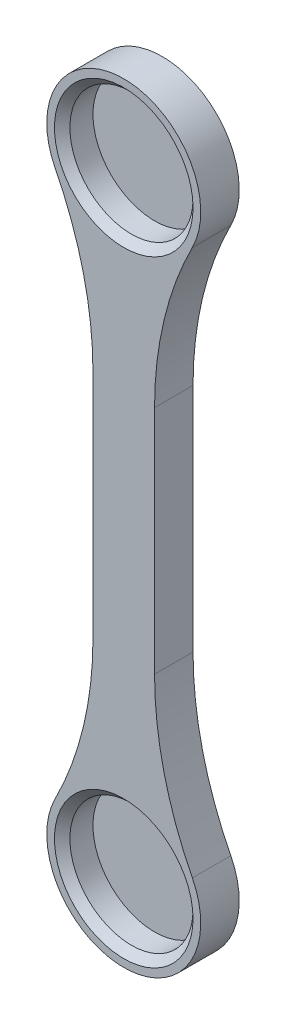
SolidWorks part; units mm, degrees
ref_plane "Plan de face" through (0, 0, 0) normal (0, 0, 1) x (1, 0, 0)
ref_plane "Plan de dessus" through (0, 0, 0) normal (0, 1, 0) x (1, 0, 0)
ref_plane "Plan de droite" through (0, 0, 0) normal (1, 0, 0) x (0, 0, -1)
sketch "Esquisse1" plane through (0, 0, 0) normal (0, 0, 1) x (1, 0, 0)
  line L0 (-10, 0) -> (-10, 80)
  line L1 (10, 0) -> (10, 80)
  arc A0 (-10, 0) -> (10, 0) centre (0, 0) ccw
  arc A1 (10, 80) -> (-10, 80) centre (0, 80) ccw
  point P9 (11.059, 55.5002)
  point P10 (0, 0)
  point P11 (0, 0)
  point P12 (-11.8706, 0)
  dimension "D1" = 80
  dimension "D2" = 10
extrude "Boss.-Extru.1" add sketch "Esquisse1" along normal blind 5
sketch "Esquisse2" plane through (0, 0, 5) normal (0, 0, 1) x (1, 0, 0)
  circle A0 centre (0, 0) radius 8
  circle A1 centre (0, 80) radius 8
  arc A2 (10, 80) -> (-10, 80) centre (0, 80) ccw construction
  point P5 (-0.6523, 60.7489)
  dimension "D1" = 16
extrude "Enlèv. mat.-Extru.1" cut sketch "Esquisse2" against normal blind 4
sketch "Esquisse3" plane through (0, 0, 5) normal (0, 0, 1) x (1, 0, 0)
  line L0 (-4, 55) -> (-4, 25)
  line L1 (-10, 40) -> (10, 40) construction
  line L2 (-10, 80) -> (-10, 0) construction
  line L3 (10, 0) -> (10, 80) construction
  line L4 (0, -55) -> (0, 55) construction
  line L5 (4, 55) -> (4, 25)
  line L6 (-10, 80) -> (-10, 0)
  line L7 (10, 0) -> (10, 80)
  arc A0 (10, 0) -> (8.9107, 4.5386) centre (0, 0) ccw
  arc A2 (-8.9107, 4.5386) -> (-4, 25) centre (-49.0833, 25) ccw
  arc A3 (8.9107, 75.4614) -> (10, 80) centre (0, 80) ccw
  arc A4 (10, 80) -> (-10, 80) centre (0, 80) ccw construction
  arc A6 (-8.9107, 75.4614) -> (-4, 55) centre (-49.0833, 55) cw
  arc A7 (8.9107, 4.5386) -> (4, 25) centre (49.0833, 25) cw
  arc A8 (8.9107, 75.4614) -> (4, 55) centre (49.0833, 55) ccw
  arc A9 (-8.9107, 4.5386) -> (-10, 0) centre (0, 0) ccw
  arc A10 (-10, 80) -> (-8.9107, 75.4614) centre (0, 80) ccw
  point P23 (0, 40)
  point P28 (-4, 40)
  dimension "D1" = 4
  dimension "D2" = 15
extrude "Enlèv. mat.-Extru.2" cut sketch "Esquisse3" against normal through all
chamfer "Chanfrein1" distance 1 angle 45 2 edges at (8, 0, 5) (8, 80, 5)
